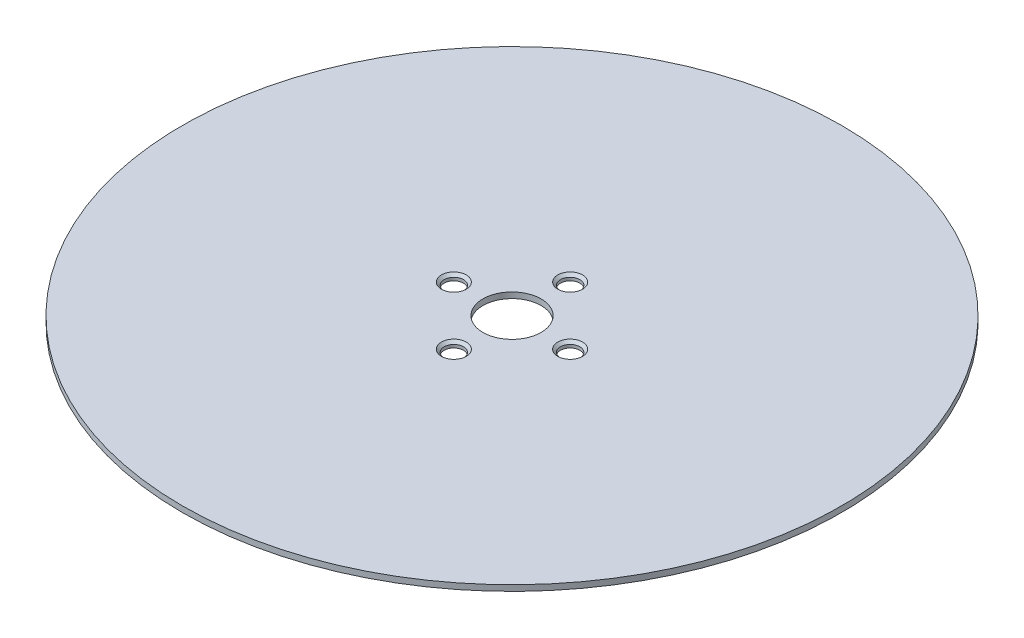
SolidWorks part; units mm, degrees
ref_plane "前视基准面" through (0, 0, 0) normal (0, 0, 1) x (1, 0, 0)
ref_plane "上视基准面" through (0, 0, 0) normal (0, 1, 0) x (1, 0, 0)
ref_plane "右视基准面" through (0, 0, 0) normal (1, 0, 0) x (0, 0, -1)
sketch "草图1" plane through (0, 0, 0) normal (0, 1, 0) x (1, 0, 0)
  line L0 (0, 0) -> (-30, 0)
  circle A0 centre (0, 0) radius 170
  circle A1 centre (0, 0) radius 15
  circle A2 centre (-30, 0) radius 5
  circle A3 centre (0, 30) radius 5
  circle A4 centre (30, 0) radius 5
  circle A5 centre (0, -30) radius 5
  point P15 (0, 0)
  dimension "D1" = 340
  dimension "D2" = 30
  dimension "D4" = 10
  dimension "D3" = 30
  dimension "D5" = 4
extrude "凸台-拉伸1" add sketch "草图1" along normal mid plane 3
hole_wizard "大小mm 暗销孔2" positions "草图4" profile "草图5" hole size "Ø1.0" standard "GB"
sketch "草图4" plane through (0, 1.5, 0) normal (0, 1, 0) x (1, 0, 0)
  point P0 (-30, 0)
  point P3 (0, 30)
  point P6 (30, 0)
  point P9 (0, -30)
sketch "草图5" plane through (-30, 1.5, 0) normal (1, 0, 0) x (0, 0, 1)
  line L0 (0, 0) -> (0, 12.7004)
  line L1 (0, 12.7004) -> (0.5, 12.4)
  line L2 (0.5, 12.4) -> (0.5, 5.9)
  line L3 (0.5, 5.9) -> (6.4, 0)
  line L5 (6.4, 0) -> (0, 0)
  line L6 (-0.5, 5.9) -> (-6.4, 0) construction
  line L10 (0, 12.7004) -> (-0.5, 12.4) construction
  line L11 (0, -6.35) -> (0, 107.95) construction
  dimension "孔直径" = 1
  dimension "孔深度" = 12.4
  dimension "近端锥形沉头孔直径" = 12.8
  dimension "近端锥形沉头孔角度" = 90
  dimension "导头角度" = 118
